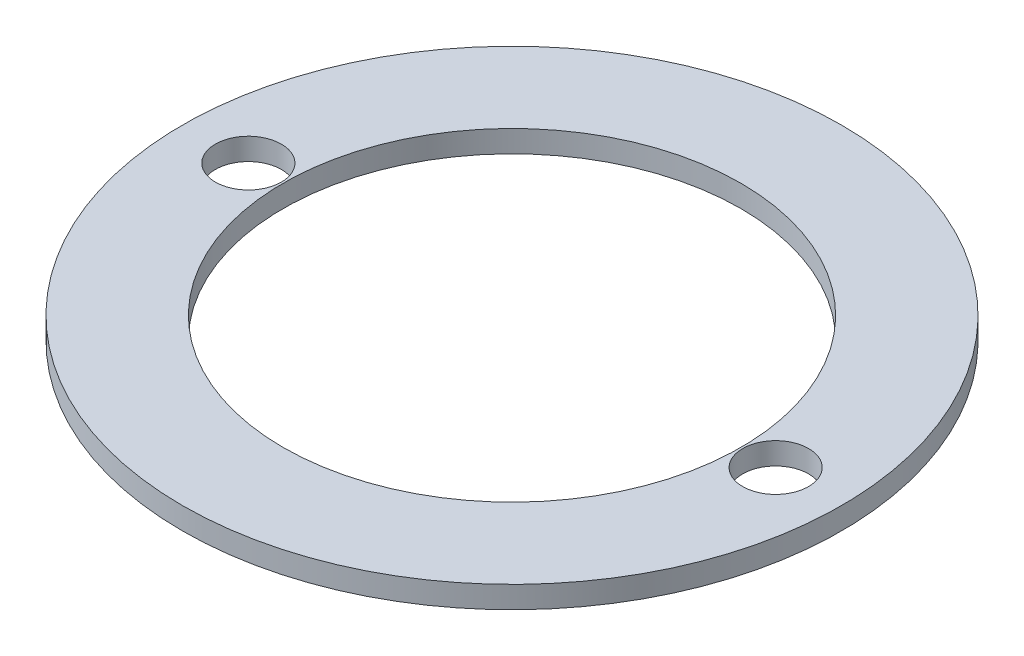
SolidWorks part; units mm, degrees
ref_plane "Front Plane" through (0, 0, 0) normal (0, 0, 1) x (1, 0, 0)
ref_plane "Top Plane" through (0, 0, 0) normal (0, 1, 0) x (1, 0, 0)
ref_plane "Right Plane" through (0, 0, 0) normal (1, 0, 0) x (0, 0, -1)
sketch "Sketch1" plane through (0, 0, 0) normal (0, 1, 0) x (1, 0, 0)
  circle A0 centre (0, 0) radius 15.875
  circle A1 centre (0, 0) radius 22.86
  circle A2 centre (-18.288, 0) radius 2.286
  circle A3 centre (18.288, 0) radius 2.286
  point P8 (0, 0)
  dimension "D1" = 31.75
  dimension "D2" = 45.72
  dimension "D4" = 4.572
  dimension "D6" = 4.572
  dimension "D3" = 18.288
  dimension "D5" = 18.288
extrude "Boss-Extrude1" add sketch "Sketch1" along normal blind 1.524
